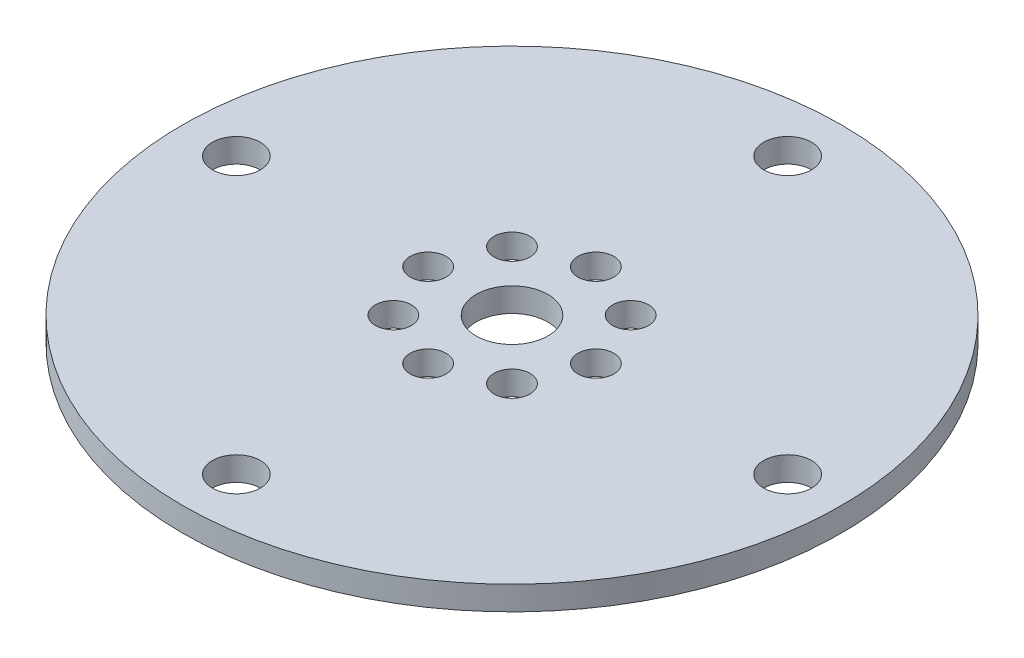
SolidWorks part; units mm, degrees
ref_plane "前视基准面" through (0, 0, 0) normal (0, 0, 1) x (1, 0, 0)
ref_plane "上视基准面" through (0, 0, 0) normal (0, 1, 0) x (1, 0, 0)
ref_plane "右视基准面" through (0, 0, 0) normal (1, 0, 0) x (0, 0, -1)
other "Configuration Table"
sketch "草图1" plane through (0, 0, 0) normal (0, 1, 0) x (1, 0, 0)
  circle A0 centre (0, 0) radius 27.5
  circle A1 centre (0, 0) radius 7 construction
  circle A2 centre (0, 7) radius 1.5
  circle A3 centre (4.9497, 4.9497) radius 1.5
  circle A4 centre (7, 0) radius 1.5
  circle A5 centre (4.9497, -4.9497) radius 1.5
  circle A6 centre (0, -7) radius 1.5
  circle A7 centre (-4.9497, -4.9497) radius 1.5
  circle A8 centre (-7, 0) radius 1.5
  circle A9 centre (-4.9497, 4.9497) radius 1.5
  circle A10 centre (0, 0) radius 3
  circle A11 centre (0, 0) radius 23 construction
  circle A12 centre (0, 23) radius 2
  circle A13 centre (23, 0) radius 2
  circle A14 centre (0, -23) radius 2
  circle A15 centre (-23, 0) radius 2
  point P22 (0, 0)
  point P34 (0, 0)
  dimension "D1" = 55
  dimension "D2" = 14
  dimension "D3" = 3
  dimension "D5" = 6
  dimension "D6" = 46
  dimension "D8" = 4
  dimension "D4" = 8
  dimension "D7" = 4
extrude "凸台-拉伸1" add sketch "草图1" along normal blind 2
